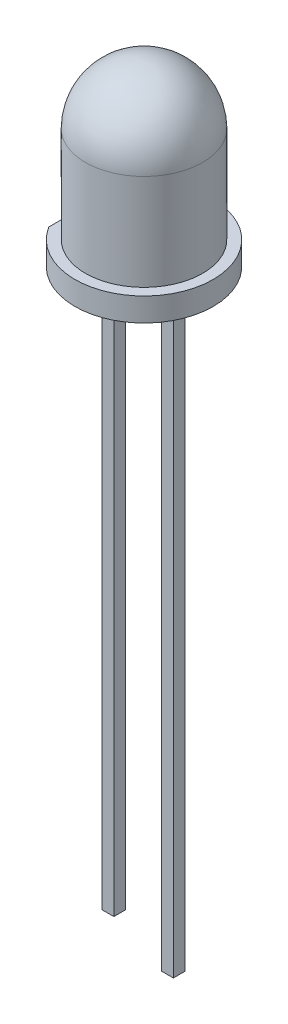
SolidWorks part; units mm, degrees
ref_plane "Alzado" through (0, 0, 0) normal (0, 0, 1) x (1, 0, 0)
ref_plane "Planta" through (0, 0, 0) normal (0, 1, 0) x (1, 0, 0)
ref_plane "Vista lateral" through (0, 0, 0) normal (1, 0, 0) x (0, 0, -1)
sketch "Croquis2" plane through (0, 0, 0) normal (1, 0, 0) x (0, 0, -1)
  line L0 (0, -1491.4716) -> (0, 1148.2312) construction
  line L1 (0, -919.5893) -> (2.95, -919.5893)
  line L2 (2.95, -919.5893) -> (2.95, -918.5893)
  line L3 (2.95, -918.5893) -> (2.5, -918.5893)
  line L4 (2.5, -918.5893) -> (2.5, -914.4893)
  line L5 (0, -919.5893) -> (0, -911.9893)
  arc A0 (2.5, -914.4893) -> (0, -911.9893) centre (0, -914.4893) ccw
  dimension "D1" = 7.6
  dimension "D2" = 1
  dimension "D3" = 2.95
  dimension "D4" = 2.5
revolve "Revolución1" add sketch "Croquis2" angle 360 about L0
sketch "Croquis3" plane through (0, -919.5893, 0) normal (0, -1, 0) x (1, 0, 0)
  line L0 (1.52, 0.2688) -> (1.52, -0.2312)
  line L1 (1.52, -0.2312) -> (1.02, -0.2312)
  line L2 (1.02, -0.2312) -> (1.02, 0.2688)
  line L3 (1.02, 0.2688) -> (1.52, 0.2688)
  line L4 (-1.02, -0.2312) -> (-1.52, -0.2312)
  line L5 (-1.52, -0.2312) -> (-1.52, 0.2688)
  line L6 (-1.52, 0.2688) -> (-1.02, 0.2688)
  line L7 (-1.02, 0.2688) -> (-1.02, -0.2312)
  circle A1 centre (0, 0) radius 2.95 construction
  dimension "D1" = 0.5
  dimension "D2" = 0.5
  dimension "D3" = 2.04
  dimension "D4" = 1.02
extrude "Saliente-Extruir3" add sketch "Croquis3" along normal blind 25.4
sketch "Croquis4" plane through (0, -918.5893, 0) normal (0, 1, 0) x (1, 0, 0)
  line L0 (-2.5, -2.5096) -> (-2.5, 3.0765)
  line L1 (-1.52, -0.2688) -> (-1.52, 0.2312) construction
  line L3 (-2.5, -2.5096) -> (-3.4125, -2.5096)
  line L4 (-3.4125, -2.5096) -> (-3.4125, 3.0765)
  line L5 (-3.4125, 3.0765) -> (-2.5, 3.0765)
  circle A0 centre (0, 0) radius 2.5 construction
extrude "Cortar-Extruir1" cut sketch "Croquis4" against normal blind 25.4
sketch "Croquis5" plane through (0, 0, 0.2688) normal (0, 0, 1) x (1, 0, 0)
  line L0 (-1.52, -943.9893) -> (-1.52, -944.9893)
  line L1 (-1.52, -944.9893) -> (-1.02, -944.9893)
  line L2 (-1.02, -944.9893) -> (-1.02, -943.9893)
  line L3 (-1.02, -943.9893) -> (-1.52, -943.9893)
  line L4 (-1.02, -944.9893) -> (-1.02, -919.5893) construction
  line L5 (-1.52, -944.9893) -> (-1.52, -919.5893) construction
  line L6 (-1.02, -944.9893) -> (-1.52, -944.9893) construction
  dimension "D1" = 1
extrude "Cortar-Extruir2" cut sketch "Croquis5" against normal up to next
